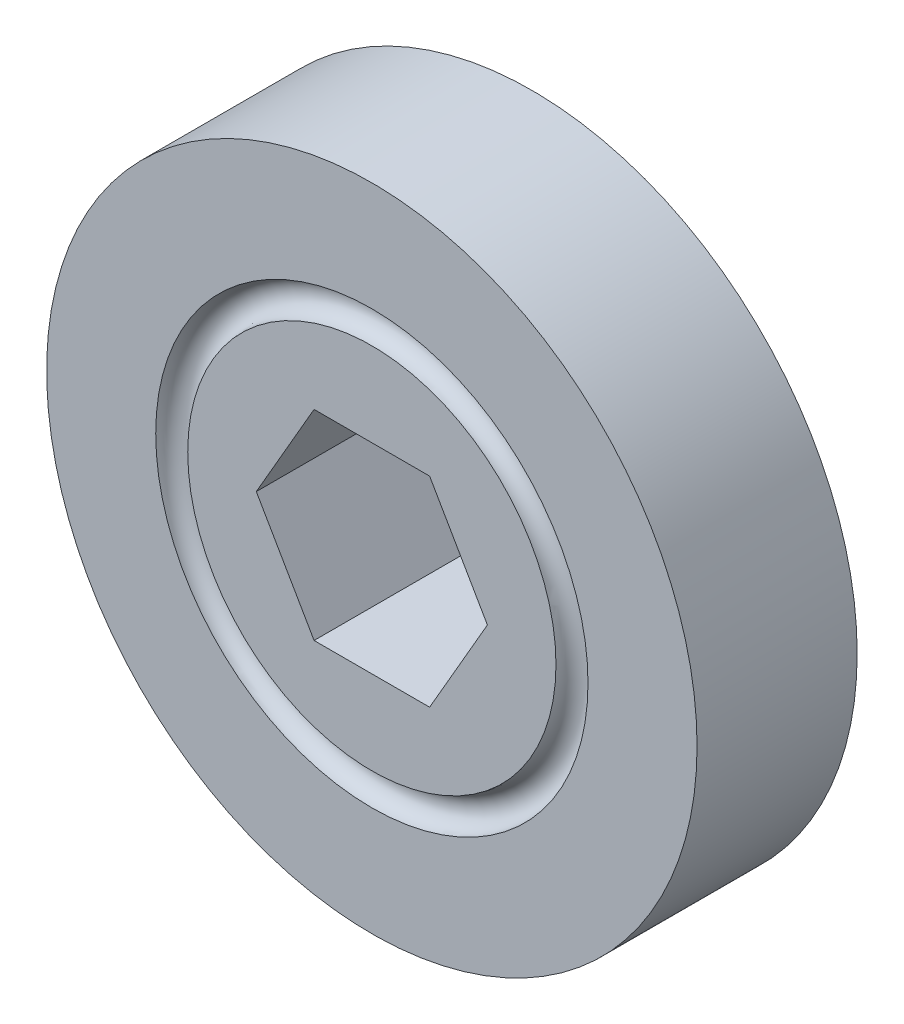
SolidWorks part; units mm, degrees
ref_plane "Front Plane" through (0, 0, 0) normal (0, 0, 1) x (1, 0, 0)
ref_plane "Top Plane" through (0, 0, 0) normal (0, 1, 0) x (1, 0, 0)
ref_plane "Right Plane" through (0, 0, 0) normal (1, 0, 0) x (0, 0, -1)
sketch "Sketch1" plane through (0, 0, 0) normal (1, 0, 0) x (0, 0, -1)
  line L0 (0, 0) -> (0, 20.6375) construction
  line L1 (-5.08, 20.6375) -> (5.08, 20.6375)
  line L2 (5.08, 20.6375) -> (5.08, 13.716)
  line L3 (5.08, 11.684) -> (5.08, 0)
  line L4 (-5.08, 11.684) -> (-5.08, 0)
  line L5 (-5.08, 20.6375) -> (-5.08, 13.716)
  line L6 (-5.08, 0) -> (5.08, 0)
  arc A0 (5.08, 13.716) -> (5.08, 11.684) centre (5.08, 12.7) ccw
  arc A1 (-5.08, 13.716) -> (-5.08, 11.684) centre (-5.08, 12.7) cw
  point P6 (0, 20.6375)
  dimension "D1" = 10.16
  dimension "D4" = 1.016
  dimension "D2" = 20.6375
  dimension "D3" = 12.7
revolve "Revolve1" add sketch "Sketch1" angle 360 about L6
sketch "Sketch2" plane through (0, 0, 5.08) normal (0, 0, 1) x (1, 0, 0)
  line L1 (-3.6662, 6.35) -> (-7.3323, 0)
  line L2 (-7.3323, 0) -> (-3.6662, -6.35)
  line L3 (-3.6662, -6.35) -> (3.6662, -6.35)
  line L4 (3.6662, -6.35) -> (7.3323, 0)
  line L5 (7.3323, 0) -> (3.6662, 6.35)
  line L6 (3.6662, 6.35) -> (-3.6662, 6.35)
  circle A0 centre (0, 0) radius 6.35 construction
  dimension "D1" = 12.7
extrude "Cut-Extrude1" cut sketch "Sketch2" against normal up to next
